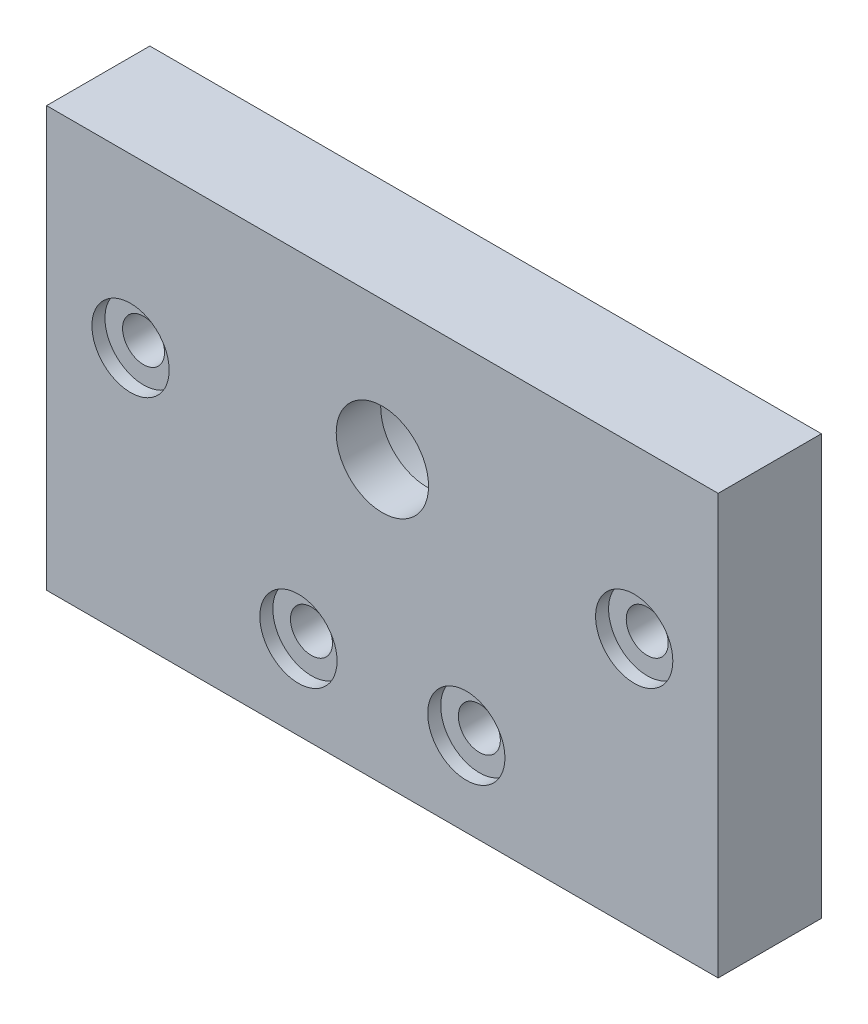
SolidWorks part; units mm, degrees
ref_plane "Front" through (0, 0, 0) normal (0, 0, 1) x (1, 0, 0)
ref_plane "Top" through (0, 0, 0) normal (0, 1, 0) x (1, 0, 0)
ref_plane "Right" through (0, 0, 0) normal (1, 0, 0) x (0, 0, -1)
sketch "Sketch1" plane through (0, 0, 0) normal (0, 0, 1) x (1, 0, 0)
  line L0 (40, 0) -> (40, 50) construction
  line L1 (0, 0) -> (80, 0)
  line L2 (0, 0) -> (0, 50)
  line L3 (0, 50) -> (80, 50)
  line L4 (80, 0) -> (80, 50)
  line L5 (0, 33.5) -> (80, 33.5) construction
  line L6 (0, 30) -> (80, 30) construction
  line L7 (0, 10) -> (80, 10) construction
  circle A0 centre (40, 33.5) radius 5.5
  circle A1 centre (10, 30) radius 2.5
  circle A2 centre (70, 30) radius 2.5
  circle A3 centre (30, 10) radius 2.5
  circle A4 centre (50, 10) radius 2.5
  point P9 (40, 33.5)
  dimension "D3" = 11
  dimension "D6" = 5
  dimension "D9" = 5
  dimension "D1" = 80
  dimension "D2" = 50
  dimension "D4" = 16.5
  dimension "D5" = 30
  dimension "D7" = 10
  dimension "D8" = 30
  dimension "D10" = 10
extrude "Boss-Extrude1" add sketch "Sketch1" along normal blind 12.3
sketch "Sketch2" plane through (0, 0, 12.3) normal (0, 0, 1) x (1, 0, 0)
  line L0 (40, 50) -> (40, 0) construction
  line L1 (80, 50) -> (0, 50) construction
  line L2 (0, 0) -> (80, 0) construction
  circle A0 centre (10, 30) radius 4.6
  circle A1 centre (70, 30) radius 4.6
  circle A2 centre (30, 10) radius 4.6
  circle A3 centre (50, 10) radius 4.6
  dimension "D1" = 9.2
  dimension "D2" = 9.2
extrude "Cut-Extrude1" cut sketch "Sketch2" against normal blind 1.55
sketch "Sketch3" plane through (0, 0, 0) normal (0, 0, -1) x (-1, 0, 0)
  circle A0 centre (-40, 33.5) radius 11
  dimension "D1" = 22
extrude "Cut-Extrude2" cut sketch "Sketch3" against normal blind 7
sketch "Sketch4" plane through (0, 50, 0) normal (0, 1, 0) x (1, 0, 0)
  line L0 (80, -6.15) -> (0, -6.15) construction
  line L1 (80, -12.3) -> (80, 0) construction
  line L2 (0, -12.3) -> (0, 0) construction
  line L3 (40, -12.3) -> (40, 0) construction
  line L4 (80, -12.3) -> (0, -12.3) construction
  line L5 (80, 0) -> (0, 0) construction
  circle A0 centre (50, -6.15) radius 2.5
  circle A1 centre (30, -6.15) radius 2.5
  dimension "D2" = 5
  dimension "D1" = 15
extrude "Cut-Extrude3" [suppressed] cut sketch "Sketch4" against normal blind 11
